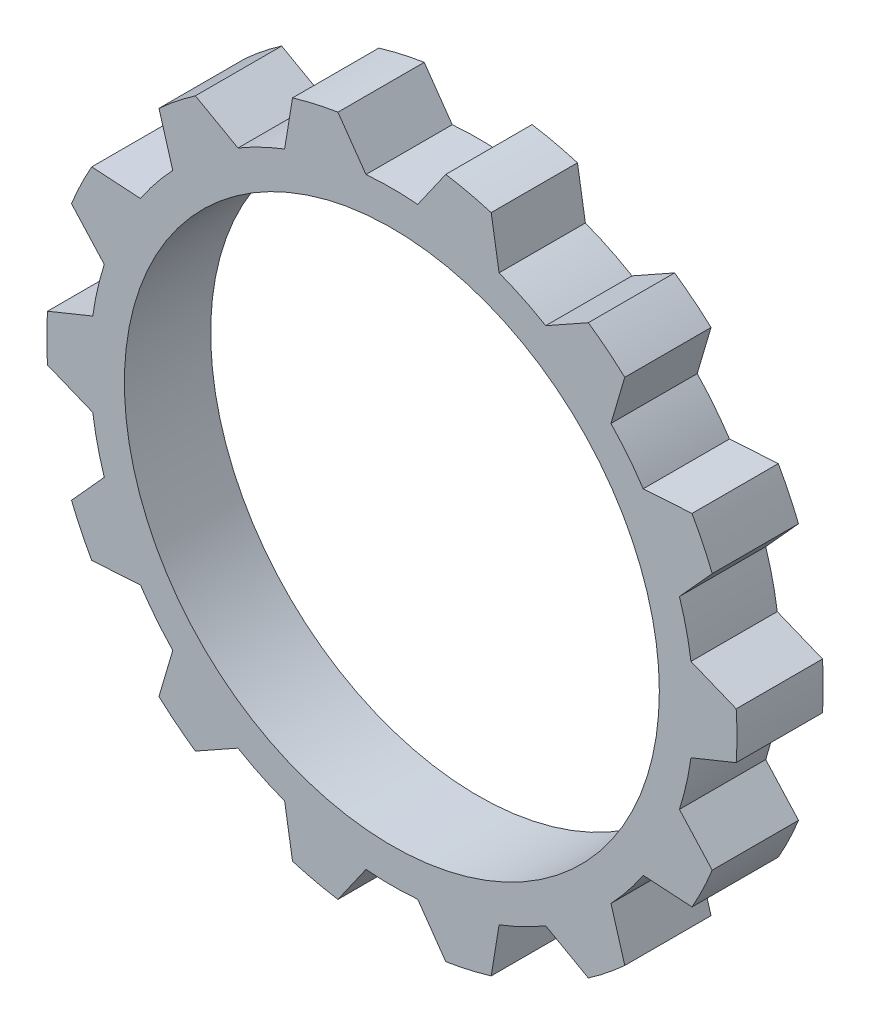
SolidWorks part; units mm, degrees
ref_plane "Front Plane" through (0, 0, 0) normal (0, 0, 1) x (1, 0, 0)
ref_plane "Top Plane" through (0, 0, 0) normal (0, 1, 0) x (1, 0, 0)
ref_plane "Right Plane" through (0, 0, 0) normal (1, 0, 0) x (0, 0, -1)
sketch "Sketch1" plane through (0, 0, 0) normal (0, 0, 1) x (1, 0, 0)
  circle A0 centre (0, 0) radius 20
  circle A1 centre (0, 0) radius 15.5
  dimension "D1" = 40
  dimension "D2" = 31
extrude "Boss-Extrude1" add sketch "Sketch1" along normal mid plane 5
sketch "Sketch2" plane through (0, 0, 2.5) normal (0, 0, 1) x (1, 0, 0)
  line L0 (0, 17.5) -> (0, 20) construction
  line L1 (-1.5, 17.4356) -> (-3.1237, 19.7545)
  line L2 (1.5, 17.4356) -> (3.1237, 19.7545)
  circle A0 centre (0, 0) radius 17.5
  circle A1 centre (0, 0) radius 20 construction
  circle A2 centre (0, 0) radius 20
  circle M6 centre (0, 0) radius 20
  dimension "D1" = 35
  dimension "D2" = 35
  dimension "D3" = 1.5
  dimension "D4" = 1.5
extrude "Cut-Extrude1" cut sketch "Sketch2" against normal blind 5 contours A0 L0 A2 L1 | L0 A0 L2 M6
pattern_circular "CirPattern1" count 14 over 360 about axis through (0, 0, 0) along (0, 0, 1) of "Cut-Extrude1"
ref_plane "Plane1" through (0, 15.5, 0) normal (0, 1, 0) x (1, 0, 0)
sketch "Sketch6" plane through (0, 15.5, 0) normal (0, 1, 0) x (1, 0, 0)
  circle A0 centre (0, 0) radius 1.5
  dimension "D1" = 3
extrude "Boss-Extrude2" add sketch "Sketch6" against normal blind 0.75
